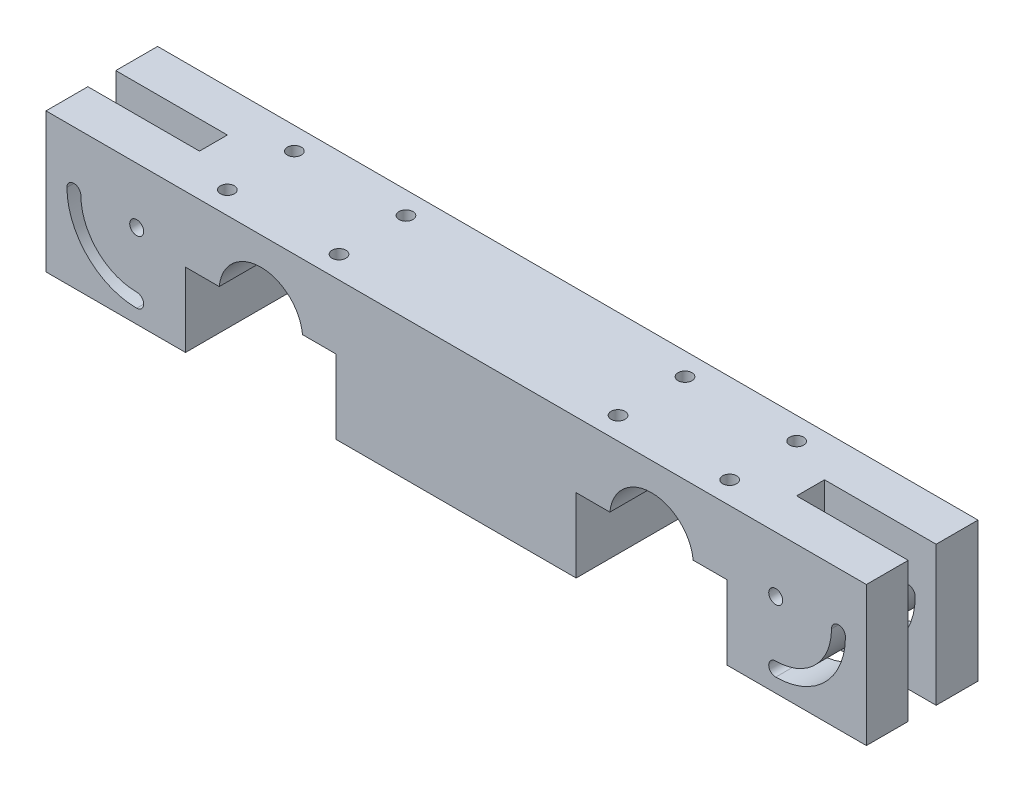
SolidWorks part; units mm, degrees
ref_plane "Front Plane" through (0, 0, 0) normal (0, 0, 1) x (1, 0, 0)
ref_plane "Top Plane" through (0, 0, 0) normal (0, 1, 0) x (1, 0, 0)
ref_plane "Right Plane" through (0, 0, 0) normal (1, 0, 0) x (0, 0, -1)
sketch "Sketch1" plane through (0, 0, 0) normal (0, 0, 1) x (1, 0, 0)
  line L1 (0, 0) -> (147, 0)
  line L2 (0, 0) -> (0, 50)
  line L3 (0, 50) -> (147, 50)
  line L4 (147, 0) -> (147, 50)
  line L5 (23, 50) -> (62, 50)
  line L6 (43, 0) -> (97, 0)
  line L7 (43, 0) -> (43, 26.5)
  line L8 (43, 26.5) -> (97, 26.5)
  line L9 (97, 0) -> (97, 26.5)
  circle A0 centre (70, 25) radius 15
  circle A1 centre (114.5, 30) radius 2.5
  arc A2 (114.5, 5) -> (139.5, 30) centre (114.5, 30) ccw
  arc A3 (114.5, 5) -> (114.5, 10) centre (114.5, 7.5) cw
  arc A4 (139.5, 30) -> (134.5, 30) centre (137, 30) ccw
  arc A5 (114.5, 10) -> (134.5, 30) centre (114.5, 30) ccw
  point P17 (114.5, 7.5)
  point P20 (137, 30)
  dimension "D3" = 30
  dimension "D4" = 25
  dimension "D9" = 5
  dimension "D1" = 50
  dimension "D2" = 50
  dimension "D5" = 70
  dimension "D6" = 26.5
  dimension "D7" = 54
  dimension "D8" = 27
  dimension "D10" = 20
  dimension "D11" = 17.5
  dimension "D12" = 25
  dimension "D13" = 2.5
  dimension "D14" = 2.5
extrude "Boss-Extrude1" add sketch "Sketch1" along normal blind 40
sketch "Sketch3" plane through (0, 50, 0) normal (0, 1, 0) x (1, 0, 0)
  line L0 (0, -40) -> (147, -40) construction
  line L1 (0, -40) -> (0, 0) construction
  line L2 (0, 0) -> (147, 0) construction
  circle A0 centre (50, -32) radius 2.5
  circle A1 centre (90, -32) radius 2.5
  circle A2 centre (50, -8) radius 2.5
  circle A3 centre (90, -8) radius 2.5
  dimension "D2" = 5
  dimension "D5" = 5
  dimension "D7" = 5
  dimension "D8" = 5
  dimension "D1" = 8
  dimension "D3" = 50
  dimension "D4" = 8
  dimension "D6" = 90
  dimension "D9" = 50
  dimension "D10" = 8
  dimension "D11" = 8
  dimension "D12" = 90
extrude "Cut-Extrude2" cut sketch "Sketch3" against normal up to surface (23.5 mm away) up to face at (49.0376, 26.5, 20)
sketch "Sketch4" plane through (0, 50, 0) normal (0, 1, 0) x (1, 0, 0)
  line L0 (147, -40) -> (147, 0) construction
  line L1 (147, -15) -> (107, -15)
  line L2 (147, -15) -> (147, -25)
  line L3 (147, -25) -> (107, -25)
  line L4 (107, -15) -> (107, -25)
  line L5 (0, 0) -> (147, 0) construction
  dimension "D1" = 40
  dimension "D2" = 10
  dimension "D3" = 15
extrude "Cut-Extrude3" cut sketch "Sketch4" against normal up to surface (50 mm away) up to face at (122, 0, 20)
mirror "Mirror2" about plane through (0, 0, 40) normal (-1, 0, 0) of "Cut-Extrude2", "Cut-Extrude3", "Boss-Extrude1"
